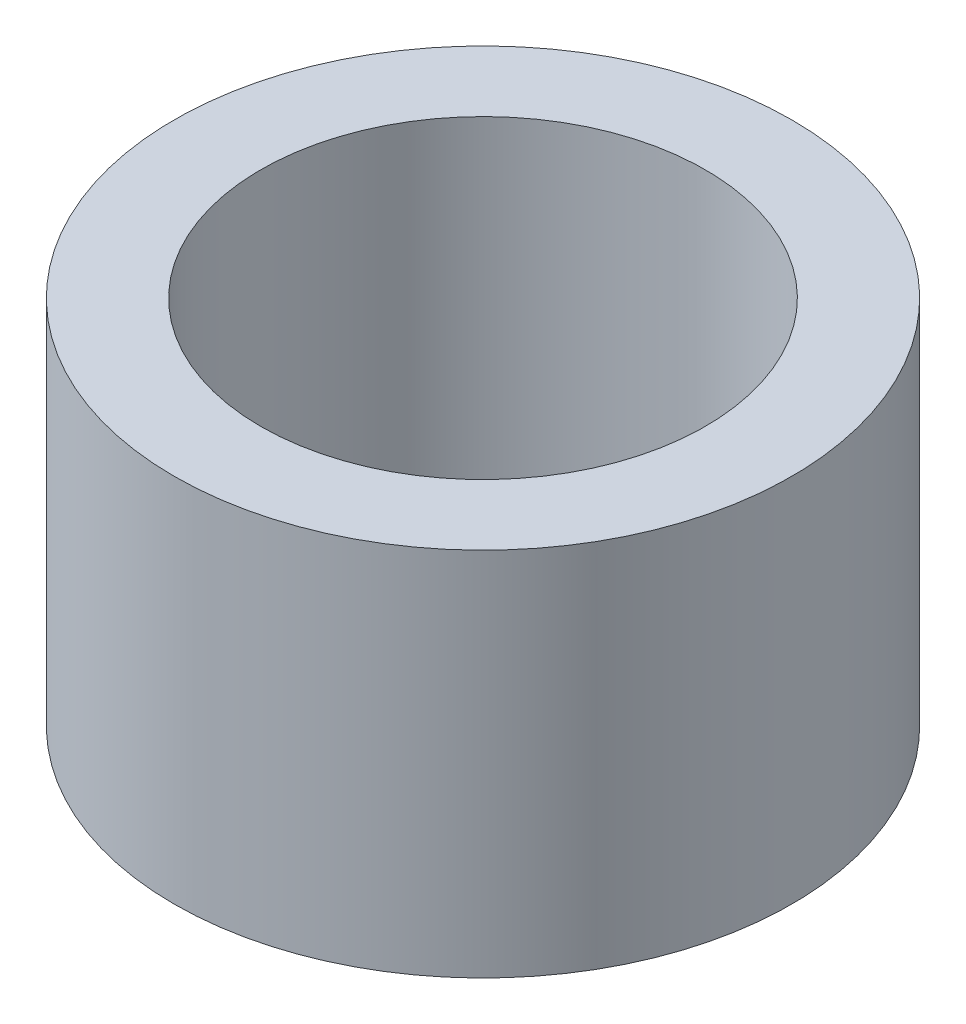
SolidWorks part; units mm, degrees
ref_plane "Front Plane" through (0, 0, 0) normal (0, 0, 1) x (1, 0, 0)
ref_plane "Top Plane" through (0, 0, 0) normal (0, 1, 0) x (1, 0, 0)
ref_plane "Right Plane" through (0, 0, 0) normal (1, 0, 0) x (0, 0, -1)
sketch "Sketch1" plane through (0, 0, 0) normal (0, 1, 0) x (1, 0, 0)
  circle A0 centre (0, 0) radius 1.8
  circle A1 centre (0, 0) radius 2.5
extrude "Boss-Extrude1" add sketch "Sketch1" along normal blind 3
